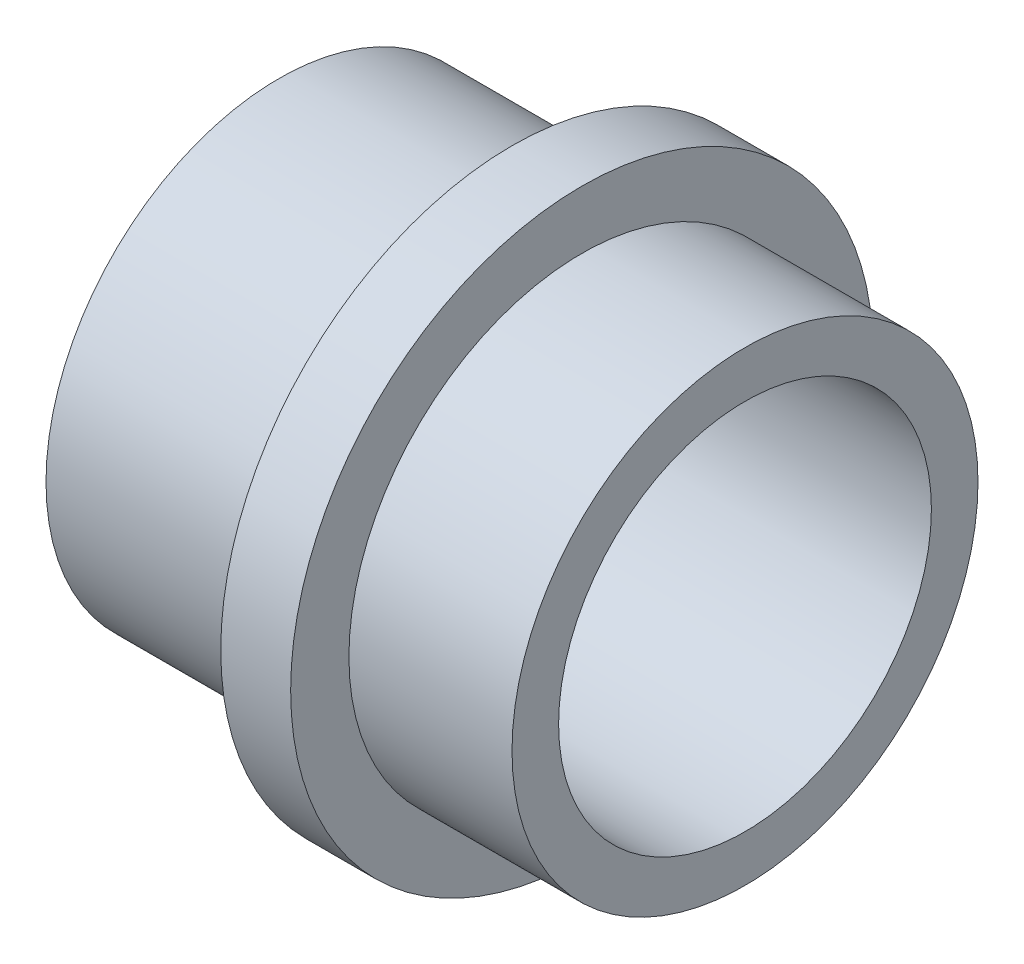
SolidWorks part; units mm, degrees
ref_plane "Front Plane" through (0, 0, 0) normal (0, 0, 1) x (1, 0, 0)
ref_plane "Top Plane" through (0, 0, 0) normal (0, 1, 0) x (1, 0, 0)
ref_plane "Right Plane" through (0, 0, 0) normal (1, 0, 0) x (0, 0, -1)
sketch "Sketch1" plane through (0, 0, 0) normal (1, 0, 0) x (0, 0, -1)
  circle A0 centre (0, 0) radius 1.27
  dimension "D1" = 2.54
extrude "Boss-Extrude1" add sketch "Sketch1" along normal blind 2.54
sketch "Sketch2" plane through (0, 0, 0) normal (0, 0, 1) x (1, 0, 0)
  line L0 (2.54, 1.27) -> (0, 1.27) construction
  line L1 (1.27, 1.27) -> (1.651, 1.27)
  line L2 (1.27, 1.27) -> (1.27, 1.5875)
  line L3 (1.27, 1.5875) -> (1.651, 1.5875)
  line L4 (1.651, 1.27) -> (1.651, 1.5875)
  line L5 (0, 1.27) -> (0, -1.27) construction
  dimension "D1" = 0.381
  dimension "D2" = 0.3175
  dimension "D3" = 1.27
revolve "Revolve1" add sketch "Sketch2" angle 360 about axis through (2.54, 0, 0) along (-1, 0, 0)
sketch "Sketch3" plane through (2.54, 0, 0) normal (1, 0, 0) x (0, 0, -1)
  circle A0 centre (0, 0) radius 1.016
  dimension "D1" = 2.032
extrude "Cut-Extrude1" cut sketch "Sketch3" against normal through all
